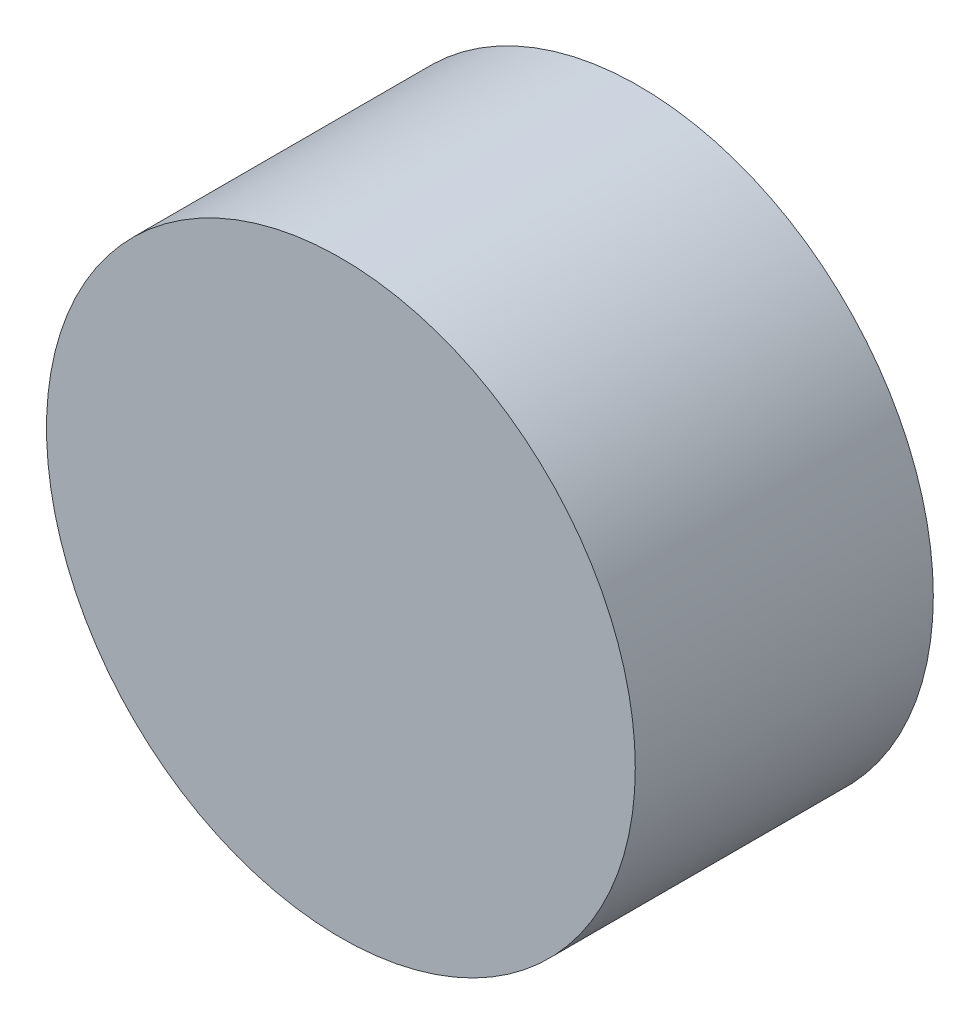
SolidWorks part; units mm, degrees
ref_plane "Front Plane" through (0, 0, 0) normal (0, 0, 1) x (1, 0, 0)
ref_plane "Top Plane" through (0, 0, 0) normal (0, 1, 0) x (1, 0, 0)
ref_plane "Right Plane" through (0, 0, 0) normal (1, 0, 0) x (0, 0, -1)
sketch "Sketch1" plane through (0, 0, 0) normal (0, 0, 1) x (1, 0, 0)
  circle A0 centre (0, 0) radius 10
extrude "Boss-Extrude1" add sketch "Sketch1" along normal blind 10.1235
